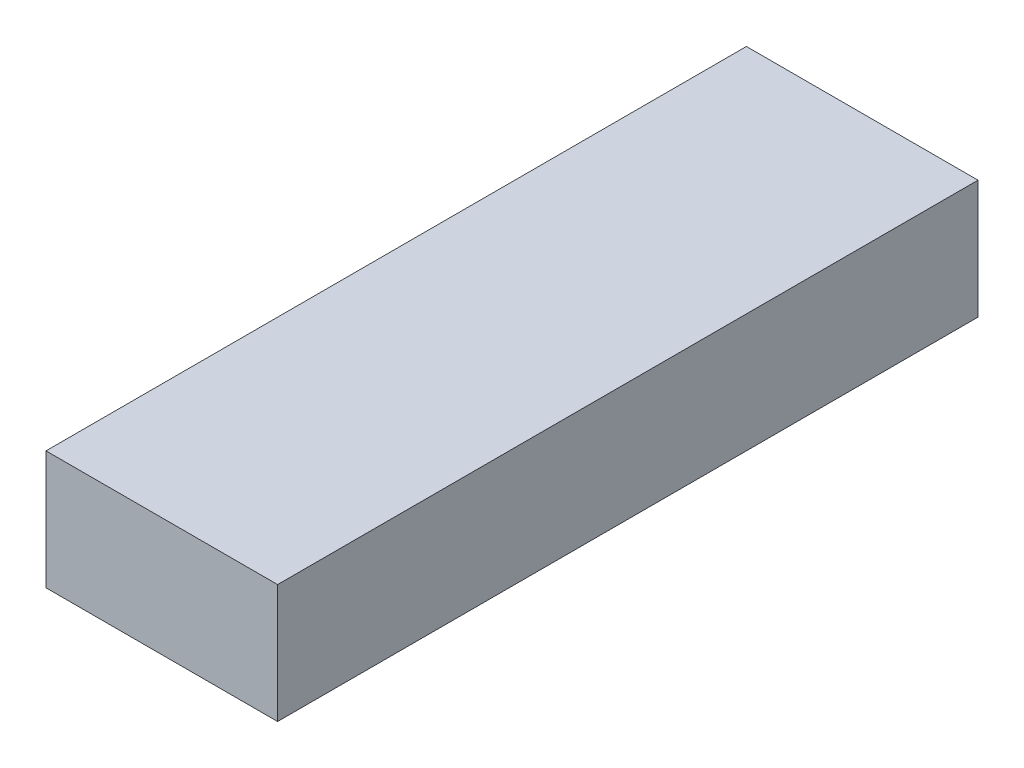
SolidWorks part; units mm, degrees
ref_plane "Front Plane" through (0, 0, 0) normal (0, 0, 1) x (1, 0, 0)
ref_plane "Top Plane" through (0, 0, 0) normal (0, 1, 0) x (1, 0, 0)
ref_plane "Right Plane" through (0, 0, 0) normal (1, 0, 0) x (0, 0, -1)
sketch "Sketch1" plane through (0, 0, 0) normal (0, 0, 1) x (1, 0, 0)
  line L1 (-20.5, 10.5) -> (20.5, 10.5)
  line L2 (-20.5, 10.5) -> (-20.5, -10.5)
  line L3 (-20.5, -10.5) -> (20.5, -10.5)
  line L4 (20.5, 10.5) -> (20.5, -10.5)
  line L5 (-20.5, 10.5) -> (20.5, -10.5) construction
  line L6 (-20.5, -10.5) -> (20.5, 10.5) construction
  point P0 (0, 0)
extrude "Boss-Extrude1" add sketch "Sketch1" along normal blind 124
